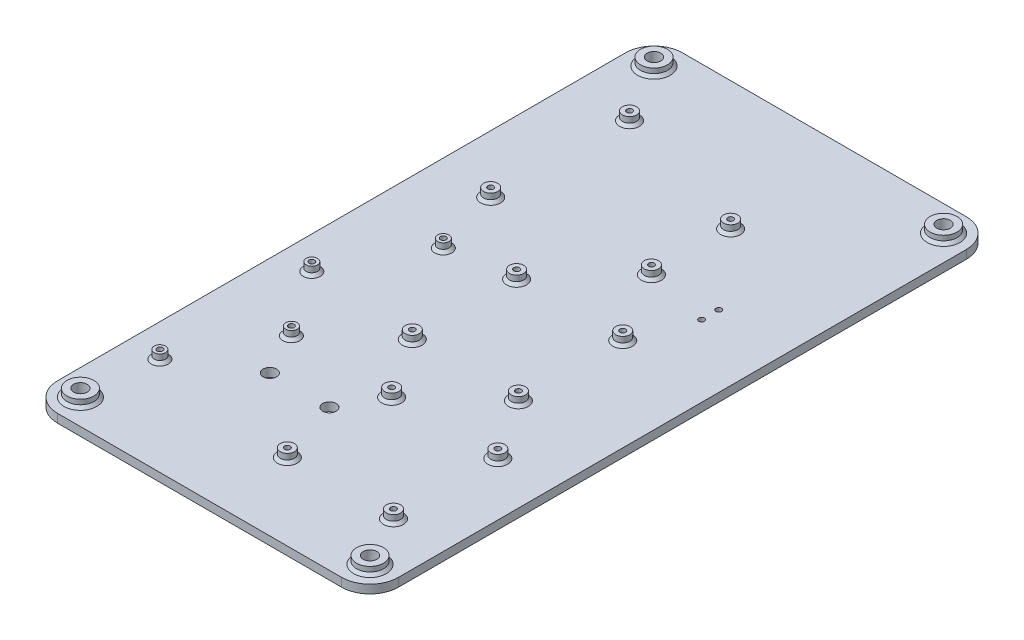
SolidWorks part; units mm, degrees
ref_plane "Front Plane" through (0, 0, 0) normal (0, 0, 1) x (1, 0, 0)
ref_plane "Top Plane" through (0, 0, 0) normal (0, 1, 0) x (1, 0, 0)
ref_plane "Right Plane" through (0, 0, 0) normal (1, 0, 0) x (0, 0, -1)
sketch "Sketch2" plane through (0, 0, 0) normal (0, 1, 0) x (1, 0, 0)
  line L7 (-50, -110) -> (50, -110)
  line L8 (-60, -100) -> (-60, 100)
  line L9 (-50, 110) -> (50, 110)
  line L10 (60, -100) -> (60, 100)
  line L11 (-60, -110) -> (60, 110) construction
  line L12 (-60, 110) -> (60, -110) construction
  arc A0 (50, 110) -> (60, 100) centre (50, 100) cw
  arc A1 (-60, 100) -> (-50, 110) centre (-50, 100) cw
  arc A2 (-50, -110) -> (-60, -100) centre (-50, -100) cw
  arc A3 (50, -110) -> (60, -100) centre (50, -100) ccw
  point P0 (0, 0)
  point P5 (0, 0)
  dimension "D3" = 10
  dimension "D1" = 220
  dimension "D2" = 120
extrude "Boss-Extrude1" add sketch "Sketch2" along normal mid plane 3
sketch "Sketch3" plane through (0, 1.5, 0) normal (0, 1, 0) x (1, 0, 0)
  circle A0 centre (41.2432, -46.2439) radius 1
  circle A1 centre (41.2432, -46.2439) radius 2.5
  circle A2 centre (3.8637, -46.2439) radius 1
  circle A3 centre (3.8637, -46.2439) radius 2.5
  circle A4 centre (3.8637, -82.9857) radius 1
  circle A5 centre (3.8637, -82.9857) radius 2.5
  circle A6 centre (41.2432, -82.9857) radius 1
  circle A7 centre (41.2432, -82.9857) radius 2.5
  circle A8 centre (-10.1363, -24.9857) radius 1
  circle A9 centre (-10.1363, -24.9857) radius 2.5
  circle A10 centre (-10.1363, 11.7561) radius 1
  circle A11 centre (-10.1363, 11.7561) radius 2.5
  circle A12 centre (27.2432, 11.7561) radius 1
  circle A13 centre (27.2432, 11.7561) radius 2.5
  circle A14 centre (27.2432, -24.9857) radius 1
  circle A15 centre (27.2432, -24.9857) radius 2.5
  circle A16 centre (-48.56, -75.45) radius 1
  circle A17 centre (-48.56, -75.45) radius 2
  circle A18 centre (-32.54, -45.15) radius 1
  circle A19 centre (-32.54, -45.15) radius 2
  circle A20 centre (-48.56, -21.95) radius 1
  circle A21 centre (-48.56, -21.95) radius 2
  circle A22 centre (-32.54, 8.35) radius 1
  circle A23 centre (-32.54, 8.35) radius 2
  circle A24 centre (-39.7, 32.2) radius 1
  circle A25 centre (-39.7, 32.2) radius 2.5
  circle A26 centre (-38.6, 80) radius 1
  circle A27 centre (-38.6, 80) radius 2.5
  circle A28 centre (12.2, 36.9) radius 1
  circle A29 centre (12.2, 36.9) radius 2.5
  circle A30 centre (12.2, 64.8) radius 1
  circle A31 centre (12.2, 64.8) radius 2.5
  circle A32 centre (-32.54, 8.35) radius 1.5 construction
  circle A33 centre (-48.56, -21.95) radius 1.5 construction
  circle A34 centre (-32.54, -45.15) radius 1.5 construction
  circle A35 centre (-48.56, -75.45) radius 1.5 construction
  point P2 (0, 0)
  point P6 (0, 0)
  point P10 (-48.56, -21.95)
  point P14 (0, 0)
  point P18 (3.8637, -46.2439)
  point P22 (41.2432, -46.2439)
  point P26 (41.2432, -82.9857)
  point P30 (3.8637, -82.9857)
  point P32 (-48.56, -75.3428)
  point P34 (0, 0)
  point P36 (-32.54, -45.15)
  point P38 (0, 0)
  point P40 (27.2432, 11.7561)
  point P42 (3.8637, -46.2439)
  point P44 (0, 0)
  point P46 (41.2432, -46.2439)
  point P50 (27.2432, -24.9857)
  point P54 (-10.1363, -24.9857)
  point P58 (-10.1363, 11.7561)
  point P62 (12.2, 64.8)
  point P66 (12.2, 36.9)
  point P67 (0, 0)
  point P70 (-38.6, 80)
  point P73 (-39.7, 32.2)
  point P76 (0, 0)
  point P77 (-32.54, 8.35)
  point P79 (-48.56, -75.45)
  point P81 (0, 0)
  dimension "D1" = 5
  dimension "D2" = 2
  dimension "D3" = 2
  dimension "D4" = 4
  dimension "D5" = 5
  dimension "D6" = 2
extrude "Boss-Extrude2" add sketch "Sketch3" along normal blind 3
hole_wizard "Ø4.8 (4.8) Diameter Hole1" positions "Sketch5" profile "Sketch6" hole size "Ø4.8" standard "ANSI Metric" end condition through all
sketch "Sketch5" plane through (0, 1.5, 0) normal (0, 1, 0) x (1, 0, 0)
  line L0 (-50, -110) -> (50, -110) construction
  line L1 (-60, 100) -> (-60, -100) construction
  line L2 (50, 110) -> (-50, 110) construction
  line L3 (60, -100) -> (60, 100) construction
  point P0 (51, 101)
  point P2 (51, -101)
  point P4 (-51, -101)
  point P6 (-51, 101)
  dimension "D1" = 9
  dimension "D2" = 9
  dimension "D3" = 9
  dimension "D4" = 9
sketch "Sketch6" plane through (51, 1.5, -101) normal (1, 0, 0) x (0, 0, 1)
  line L0 (0, 0) -> (0, 3)
  line L1 (0, 3) -> (2.4, 3)
  line L2 (2.4, 3) -> (2.4, 0)
  line L5 (2.4, 0) -> (0, 0)
  line L11 (0, -6.35) -> (0, 107.95) construction
  dimension "Thru Hole Dia." = 4.8
  dimension "Thru Hole Depth" = 3
sketch "Sketch7" plane through (0, 1.5, 0) normal (0, 1, 0) x (1, 0, 0)
  circle A0 centre (51, 101) radius 2.4 construction
  circle A1 centre (-51, 101) radius 2.4 construction
  circle A2 centre (-51, -101) radius 2.4 construction
  circle A3 centre (51, -101) radius 2.4 construction
  circle A4 centre (51, 101) radius 2.4
  circle A5 centre (-51, 101) radius 2.4
  circle A6 centre (-51, -101) radius 2.4
  circle A7 centre (51, -101) radius 2.4
  circle A8 centre (51, 101) radius 4.75
  circle A9 centre (-51, 101) radius 4.75
  circle A10 centre (-51, -101) radius 4.75
  circle A11 centre (51, -101) radius 4.75
  dimension "D1" = 9.5
extrude "Boss-Extrude3" add sketch "Sketch7" along normal blind 2.7
hole_wizard "Ø2.0mm Dowel Hole1" positions "Sketch12" profile "Sketch13" hole size "Ø2.0" standard "ANSI Metric" end condition through all
sketch "Sketch12" plane through (0, 1.5, 0) normal (0, 1, 0) x (1, 0, 0)
  point P0 (27.2432, -24.9857)
  point P3 (27.2432, 11.7561)
  point P6 (-10.1363, -24.9857)
  point P9 (-10.1363, 11.7561)
  point P12 (3.8637, -46.2439)
  point P15 (41.2432, -46.2439)
  point P18 (41.2432, -82.9857)
  point P21 (3.8637, -82.9857)
  point P24 (12.2, 36.9)
  point P27 (12.2, 64.8)
  point P30 (-38.6, 80)
  point P33 (-39.7, 32.2)
  point P36 (-32.54, 8.35)
  point P39 (-48.56, -21.95)
  point P42 (-48.56, -75.45)
  point P45 (-32.54, -45.15)
  point P49 (34.8, 38)
  point P52 (34.8, 32)
  point P62 (3.8637, -46.2439)
  point P64 (12.2, 64.8)
  point P66 (34.8, 38)
  point P68 (34.8, 32)
sketch "Sketch13" plane through (27.2432, 1.5, 24.9857) normal (1, 0, 0) x (0, 0, 1)
  line L0 (0, 0) -> (0, 3)
  line L1 (0, 3) -> (1, 3)
  line L2 (1, 3) -> (1, 0)
  line L5 (1, 0) -> (0, 0)
  line L11 (0, -6.35) -> (0, 107.95) construction
  dimension "Thru Hole Dia." = 2
  dimension "Thru Hole Depth" = 3
chamfer "Chamfer1" distance 1 angle 45 20 edges at (51, 1.5, 96.25) (41.2432, 1.5, 80.4857) (3.8637, 1.5, 80.4857) (-51, 1.5, 96.25) (-48.56, 1.5, 73.45) (3.8637, 1.5, 43.7439) (41.2432, 1.5, 43.7439) (27.2432, 1.5, 22.4857) (-10.1363, 1.5, 22.4857) (-32.54, 1.5, 43.15) (-48.56, 1.5, 19.95) (-39.7, 1.5, -34.7) (-32.54, 1.5, -10.35) (-10.1363, 1.5, -14.2561) (27.2432, 1.5, -14.2561) (12.2, 1.5, -39.4) (12.2, 1.5, -67.3) (-38.6, 1.5, -82.5) (-51, 1.5, -105.75) (51, 1.5, -105.75)
ref_plane "Plane1" through (0, 0, -60) normal (0, 0, -1) x (-1, 0, 0)
ref_plane "Plane2" through (0, 0, 52.5) normal (0, 0, 1) x (1, 0, 0)
sketch "Sketch15" plane through (0, 1.5, 0) normal (0, 1, 0) x (1, 0, 0)
  line L0 (-8, -71.3) -> (-8, -49.3) construction
  line L2 (-4, -60.3) -> (-8, -60.3) construction
  line L3 (-21, -49.3) -> (-21, -70.8) construction
  circle A0 centre (-4, -60.3) radius 2.3812
  circle A1 centre (-25, -60.3) radius 2.3813
  dimension "D1" = 4.7625
  dimension "D2" = 4
  dimension "D3" = 4
extrude "Cut-Extrude1" cut sketch "Sketch15" against normal through all
